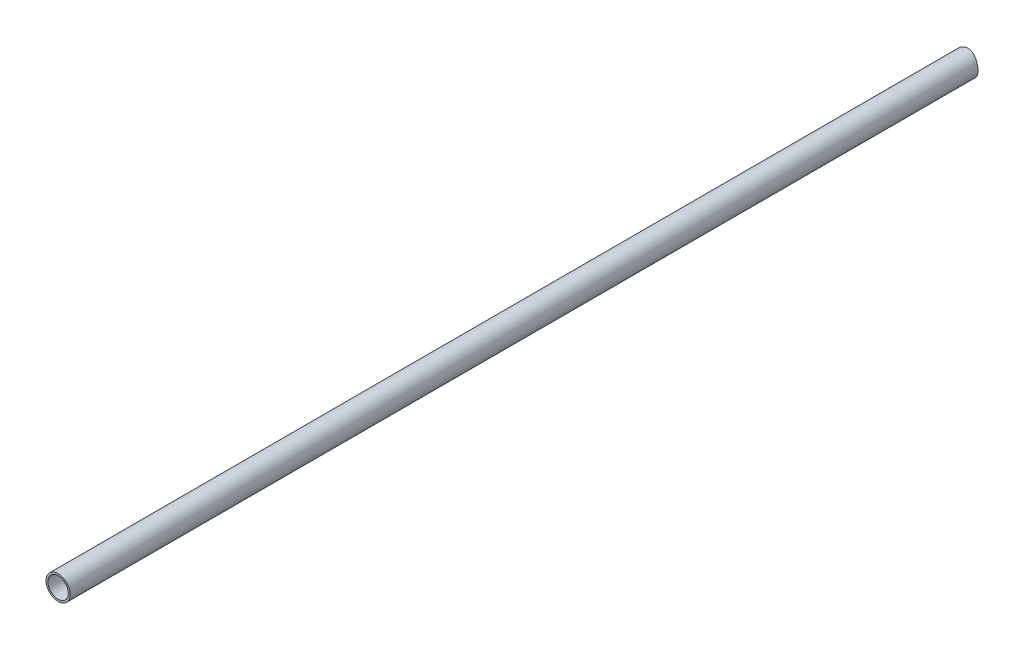
SolidWorks part; units mm, degrees
material "ASTM A36 Steel"
ref_plane "Front Plane" through (0, 0, 0) normal (0, 0, 1) x (1, 0, 0)
ref_plane "Top Plane" through (0, 0, 0) normal (0, 1, 0) x (1, 0, 0)
ref_plane "Right Plane" through (0, 0, 0) normal (1, 0, 0) x (0, 0, -1)
sketch "Sketch1" plane through (0, 0, 0) normal (0, 0, 1) x (1, 0, 0)
  circle A0 centre (0, 0) radius 13.35
  circle A1 centre (0, 0) radius 11.24
  dimension "D1" = 26.7
  dimension "D2" = 2.11
extrude "Boss-Extrude1" add sketch "Sketch1" along normal blind 1100
sketch "Sketch2" plane through (0, 0, 0) normal (1, 0, 0) x (0, 0, -1)
  circle A0 centre (0, 0) radius 40
  dimension "D1" = 80
extrude "Cut-Extrude1" cut sketch "Sketch2" against normal through all both and the other way through all
sketch "Sketch3" plane through (0, 0, 0) normal (1, 0, 0) x (0, 0, -1)
  circle A0 centre (0, 0) radius 1042
  circle A1 centre (0, 0) radius 2231.3625
  dimension "D1" = 2084
extrude "Cut-Extrude2" cut sketch "Sketch3" against normal through all both and the other way through all
